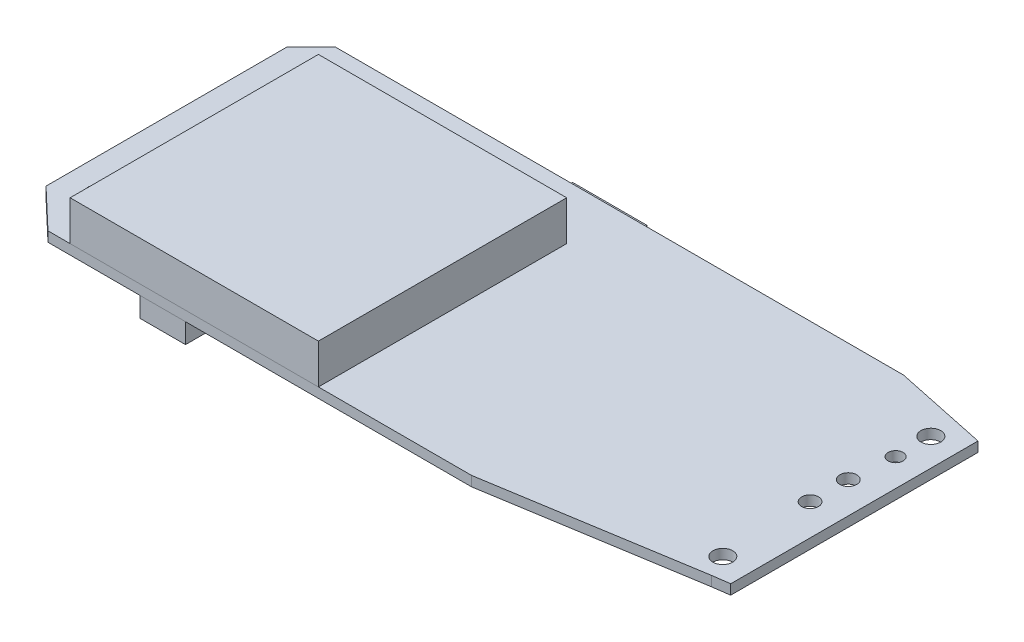
SolidWorks part; units mm, degrees
ref_plane "Front Plane" through (0, 0, 0) normal (0, 0, 1) x (1, 0, 0)
ref_plane "Top Plane" through (0, 0, 0) normal (0, 1, 0) x (1, 0, 0)
ref_plane "Right Plane" through (0, 0, 0) normal (1, 0, 0) x (0, 0, -1)
sketch "Sketch1" plane through (0, 0, 0) normal (0, 1, 0) x (1, 0, 0)
  line L0 (-32.175, 15.25) -> (25.075, 15.25)
  line L1 (-34.575, 15.25) -> (34.575, 15.25) construction
  line L2 (-34.575, 15.25) -> (-34.575, -15.25) construction
  line L3 (-34.575, -15.25) -> (34.575, -15.25) construction
  line L4 (34.575, 15.25) -> (34.575, -15.25) construction
  line L5 (-34.575, 15.25) -> (34.575, -15.25) construction
  line L6 (-34.575, -15.25) -> (34.575, 15.25) construction
  line L7 (25.075, 15.25) -> (34.575, 13.25)
  line L8 (34.575, 13.25) -> (34.575, -11.65)
  line L9 (34.575, -11.65) -> (32.875, -11.89)
  line L10 (32.875, -11.89) -> (12.075, -15.25)
  line L11 (12.075, -15.25) -> (-30.575, -15.25)
  line L12 (-30.575, -15.25) -> (-34.575, -11.45)
  line L13 (-34.575, -11.45) -> (-34.575, 12.85)
  line L14 (-34.575, 12.85) -> (-32.175, 15.25)
  line L15 (31.795, 12.2805) -> (35.1386, 12.2805) construction
  line L16 (31.795, -10.6695) -> (35.1386, -10.6695) construction
  line L17 (32.265, -0.4995) -> (32.265, 3.3505) construction
  line L18 (31.795, 6.9805) -> (35.7725, 6.9805) construction
  line L19 (32.795, 11.2805) -> (32.795, 10.1462) construction
  line L20 (31.415, -1.3495) -> (36.9042, -1.3495) construction
  line L21 (32.4568, 12.1631) -> (29.5874, 12.7671) construction
  line L22 (-32.375, -9.43) -> (-32.375, -6.2927) construction
  line L23 (-31.375, -5.16) -> (-28.4237, -5.16) construction
  line L24 (-31.375, -10.43) -> (-27.4386, -10.43) construction
  line L25 (-31.375, -8.43) -> (-27.4386, -8.43) construction
  circle A0 centre (31.795, 11.2805) radius 1
  circle A1 centre (31.795, -9.6695) radius 1
  circle A2 centre (31.415, -0.4995) radius 0.85
  circle A3 centre (31.415, 3.3505) radius 0.85
  circle A4 centre (31.795, 7.7305) radius 0.75
  circle A5 centre (-31.375, -9.43) radius 1
  circle A6 centre (-31.375, -5.91) radius 0.75
  point P0 (0, 0)
  dimension "D13" = 2
  dimension "D15" = 1.5
  dimension "D16" = 1.7
  dimension "D1" = 69.15
  dimension "D2" = 30.5
  dimension "D3" = 24.9
  dimension "D4" = 9.5
  dimension "D5" = 22.5
  dimension "D6" = 27.14
  dimension "D7" = 2
  dimension "D8" = 1.7
  dimension "D9" = 2.4
  dimension "D10" = 2.4
  dimension "D11" = 3.8
  dimension "D12" = 4
  dimension "D14" = 22.95
  dimension "D17" = 2.31
  dimension "D18" = 3.85
  dimension "D19" = 5.3
  dimension "D20" = 1.78
  dimension "D21" = 13.63
  dimension "D22" = 1.5
  dimension "D23" = 2.2
  dimension "D24" = 5.27
  dimension "D25" = 23.68
extrude "Boss-Extrude1" add sketch "Sketch1" along normal blind 1
sketch "Sketch2" plane through (0, 1, 0) normal (0, 1, 0) x (1, 0, 0)
  line L0 (-34.575, 12.85) -> (-34.575, -11.45) construction
  line L1 (-28.345, 9.75) -> (-3.345, 9.75)
  line L2 (-28.345, 9.75) -> (-28.345, -15.25)
  line L3 (-28.345, -15.25) -> (-3.345, -15.25)
  line L4 (-3.345, 9.75) -> (-3.345, -15.25)
  line L5 (-28.345, 9.75) -> (-3.345, -15.25) construction
  line L6 (-28.345, -15.25) -> (-3.345, 9.75) construction
  line L7 (-30.575, -15.25) -> (12.075, -15.25) construction
  point P0 (-15.845, -2.75)
  dimension "D1" = 25
  dimension "D2" = 6.23
extrude "Boss-Extrude2" add sketch "Sketch2" along normal blind 4 separate body
sketch "Sketch3" plane through (0, 0, 0) normal (0, -1, 0) x (-1, 0, 0)
  line L0 (-25.075, 15.25) -> (32.175, 15.25) construction
  line L1 (27.395, -1.15) -> (11.545, -1.15)
  line L2 (27.395, -1.15) -> (27.395, 15.25)
  line L3 (27.395, 15.25) -> (11.545, 15.25)
  line L4 (11.545, -1.15) -> (11.545, 15.25)
  line L5 (27.395, -1.15) -> (11.545, 15.25) construction
  line L6 (27.395, 15.25) -> (11.545, -1.15) construction
  line L7 (34.575, 12.85) -> (34.575, -11.45) construction
  point P0 (19.47, 7.05)
  dimension "D1" = 15.85
  dimension "D2" = 16.4
  dimension "D3" = 7.18
extrude "Boss-Extrude3" add sketch "Sketch3" along normal blind 1.5 separate body
sketch "Sketch4" plane through (0, 0, 0) normal (0, -1, 0) x (1, 0, 0)
  line L0 (25.075, -15.25) -> (-32.175, -15.25) construction
  line L1 (-9.375, -11.09) -> (-1.875, -11.09)
  line L2 (-9.375, -11.09) -> (-9.375, -16.39)
  line L3 (-9.375, -16.39) -> (-1.875, -16.39)
  line L4 (-1.875, -11.09) -> (-1.875, -16.39)
  line L5 (-9.375, -11.09) -> (-1.875, -16.39) construction
  line L6 (-9.375, -16.39) -> (-1.875, -11.09) construction
  line L7 (-34.575, -12.85) -> (-34.575, 11.45) construction
  point P0 (-5.625, -13.74)
  point P5 (-9.22, -16.2089)
  dimension "D1" = 5.3
  dimension "D2" = 7.5
  dimension "D3" = 1.14
  dimension "D4" = 32.7
extrude "Boss-Extrude4" add sketch "Sketch4" along normal blind 2.5 separate body
sketch "Sketch5" plane through (0, 0, 0) normal (0, -1, 0) x (1, 0, 0)
  line L0 (-30.575, 15.25) -> (12.075, 15.25) construction
  line L1 (-21.285, 15.25) -> (-16.725, 15.25)
  line L2 (-21.285, 15.25) -> (-21.285, 12.85)
  line L3 (-21.285, 12.85) -> (-16.725, 12.85)
  line L4 (-16.725, 15.25) -> (-16.725, 12.85)
  line L5 (-21.285, 15.25) -> (-16.725, 12.85) construction
  line L6 (-21.285, 12.85) -> (-16.725, 15.25) construction
  line L7 (-34.575, -12.85) -> (-34.575, 11.45) construction
  point P0 (-19.8431, 15.25)
  dimension "D1" = 4.56
  dimension "D2" = 2.4
  dimension "D3" = 17.85
extrude "Boss-Extrude5" add sketch "Sketch5" along normal blind 2 separate body
